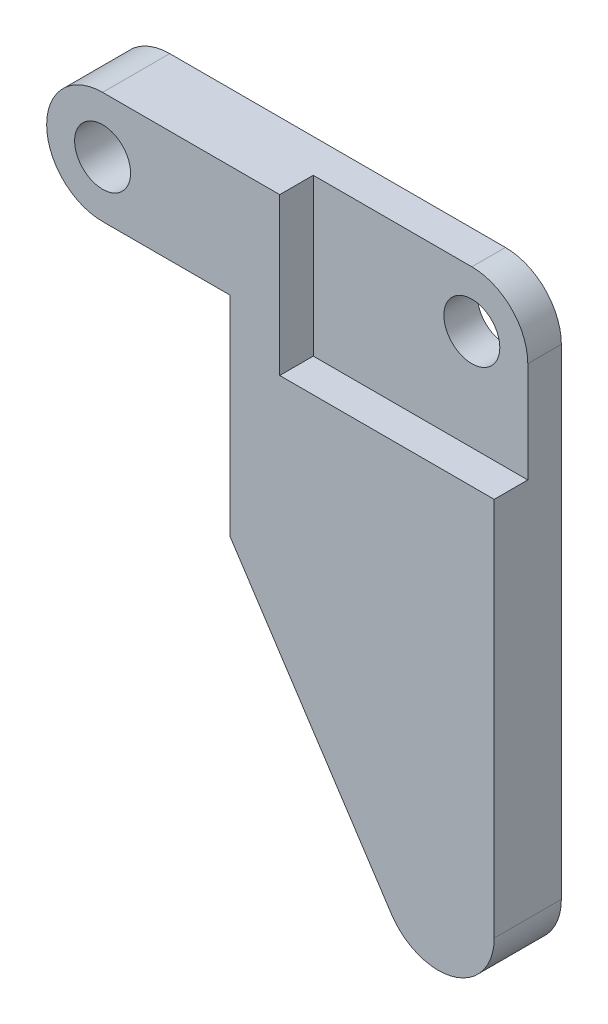
SolidWorks part; units mm, degrees
ref_plane "Front Plane" through (0, 0, 0) normal (0, 0, 1) x (1, 0, 0)
ref_plane "Top Plane" through (0, 0, 0) normal (0, 1, 0) x (1, 0, 0)
ref_plane "Right Plane" through (0, 0, 0) normal (1, 0, 0) x (0, 0, -1)
sketch "Sketch1" plane through (0, 0, 0) normal (0, 0, 1) x (1, 0, 0)
  line L0 (0, 0) -> (30, 0) construction
  line L1 (0, 0) -> (30, 0) construction
  line L2 (0, 5) -> (30, 5)
  line L3 (0, -5) -> (30, -5)
  line L4 (35, 0) -> (35, -42.9576)
  line L5 (25.8178, -45.6979) -> (11.3945, -23.6852)
  line L6 (11.3945, -23.6852) -> (11.3945, -5)
  arc A0 (0, 5) -> (0, -5) centre (0, 0) ccw
  arc A1 (30, -5) -> (30, 5) centre (30, 0) ccw
  arc A2 (35, -42.9576) -> (25.8178, -45.6979) centre (30, -42.9576) cw
  circle A3 centre (0, 0) radius 2.5
  circle A4 centre (30, 0) radius 2.5
  point P3 (15, 0)
  dimension "D2" = 5
  dimension "D3" = 5
  dimension "D1" = 30
extrude "Boss-Extrude1" add sketch "Sketch1" along normal blind 6 contours A1 L2 A0 L3 A4 A3 | A2 L4 A1 L3 L6 L5
sketch "Sketch2" plane through (0, 0, 6) normal (0, 0, 1) x (1, 0, 0)
  line L0 (15.8288, 5) -> (15.8288, -8.9991)
  line L1 (0, 5) -> (30, 5) construction
  line L2 (15.8288, -8.9991) -> (35, -8.9991)
  line L3 (35, 0) -> (35, -42.9576) construction
  line L4 (35, -8.9991) -> (35, 0)
  line L6 (30, 5) -> (15.8288, 5)
extrude "Cut-Extrude1" cut sketch "Sketch2" against normal blind 3 and the other way through all
